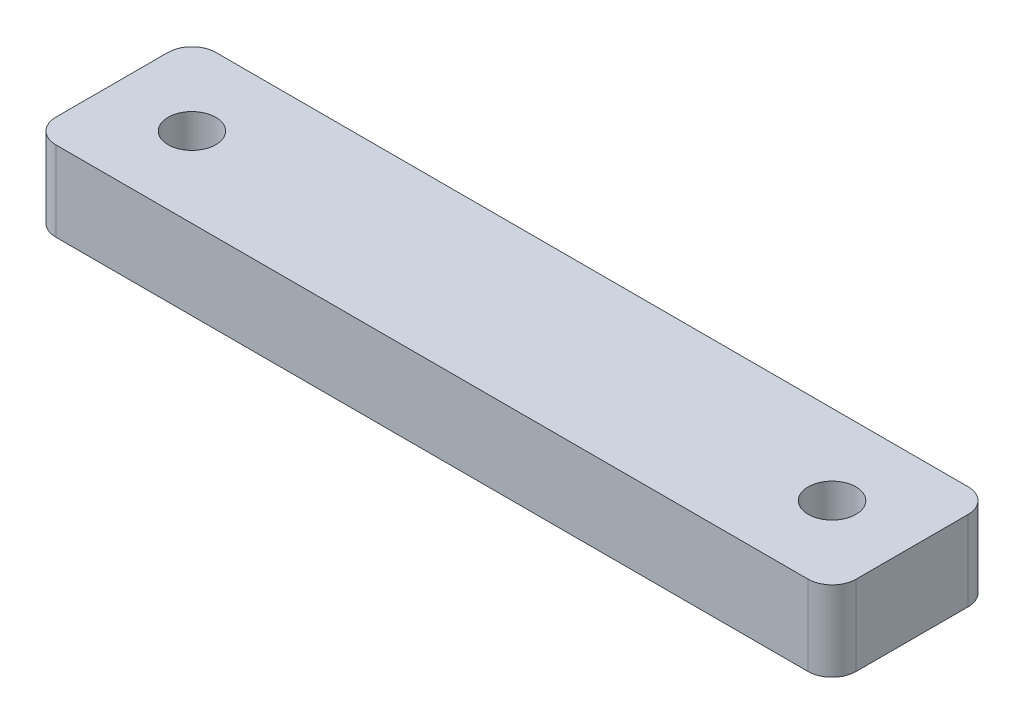
SolidWorks part; units mm, degrees
ref_plane "Front Plane" through (0, 0, 0) normal (0, 0, 1) x (1, 0, 0)
ref_plane "Top Plane" through (0, 0, 0) normal (0, 1, 0) x (1, 0, 0)
ref_plane "Right Plane" through (0, 0, 0) normal (1, 0, 0) x (0, 0, -1)
sketch "Sketch1" plane through (0, 0, 0) normal (0, 1, 0) x (1, 0, 0)
  line L1 (3.81, 0) -> (123.19, 0)
  line L2 (0, 3.81) -> (0, 21.59)
  line L3 (3.81, 25.4) -> (123.19, 25.4)
  line L4 (127, 3.81) -> (127, 21.59)
  arc A0 (127, 3.81) -> (123.19, 0) centre (123.19, 3.81) cw
  arc A1 (127, 21.59) -> (123.19, 25.4) centre (123.19, 21.59) ccw
  arc A2 (3.81, 0) -> (0, 3.81) centre (3.81, 3.81) cw
  arc A3 (3.81, 25.4) -> (0, 21.59) centre (3.81, 21.59) ccw
  circle A4 centre (12.7, 12.7) radius 3.782
  circle A5 centre (114.3, 12.7) radius 3.7909
  point P9 (127, 25.4)
  point P12 (0, 0)
  point P15 (0, 25.4)
  dimension "D3" = 3.81
  dimension "D1" = 25.4
  dimension "D2" = 127
  dimension "D4" = 12.7
  dimension "D5" = 12.7
extrude "Boss-Extrude1" add sketch "Sketch1" along normal blind 12.7
